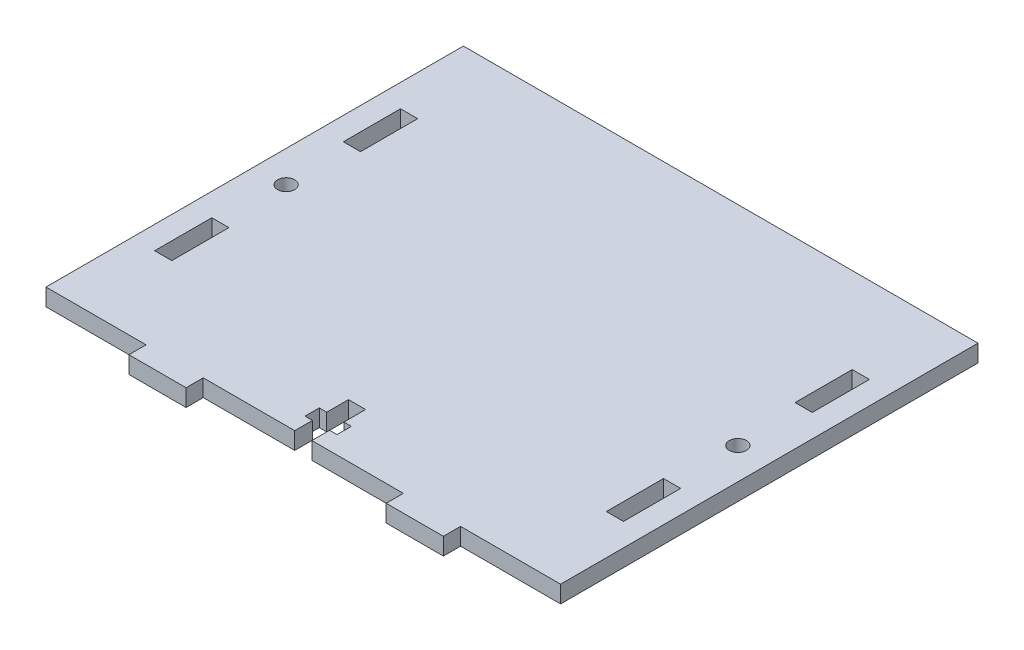
SolidWorks part; units mm, degrees
ref_plane "Front Plane" through (0, 0, 0) normal (0, 0, 1) x (1, 0, 0)
ref_plane "Top Plane" through (0, 0, 0) normal (0, 1, 0) x (1, 0, 0)
ref_plane "Right Plane" through (0, 0, 0) normal (1, 0, 0) x (0, 0, -1)
sketch "Sketch1" plane through (0, 0, 0) normal (0, 1, 0) x (1, 0, 0)
  line L0 (-72.5, 0) -> (-72.5, -3)
  line L1 (0, 0) -> (-17.5, 0)
  line L2 (0, 0) -> (0, 73)
  line L3 (0, 73) -> (-90, 73)
  line L4 (-90, 0) -> (-90, 73)
  line L5 (-72.5, -3) -> (-62.5, -3)
  line L6 (-62.5, -3) -> (-62.5, 0)
  line L7 (-72.5, 0) -> (-90, 0)
  line L8 (-45, 73) -> (-45, 9.4) construction
  line L9 (-17.5, 0) -> (-17.5, -3)
  line L10 (-17.5, -3) -> (-27.5, -3)
  line L11 (-27.5, -3) -> (-27.5, 0)
  line L12 (-27.5, 0) -> (-43.5, 0)
  line L13 (-46.5, 0) -> (-46.5, 3.1)
  line L14 (-46.5, 3.1) -> (-47.8, 3.1)
  line L15 (-47.8, 3.1) -> (-47.8, 5.6)
  line L16 (-47.8, 5.6) -> (-46.5, 5.6)
  line L17 (-46.5, -0.4668) -> (-46.5, 3.1)
  line L18 (-46.5, 5.6) -> (-46.5, 9.4)
  line L19 (-46.5, 9.4) -> (-43.5, 9.4)
  line L20 (-43.5, 9.4) -> (-43.5, 5.6)
  line L21 (-43.5, 5.6) -> (-42.2, 5.6)
  line L22 (-42.2, 5.6) -> (-42.2, 3.1)
  line L23 (-42.2, 3.1) -> (-43.5, 3.1)
  line L24 (-43.5, 3.1) -> (-43.5, 0)
  line L25 (-46.5, 0) -> (-62.5, 0)
  line L26 (-83, 15) -> (-86, 15)
  line L27 (-4, 15) -> (-4, 25)
  line L28 (-4, 25) -> (-7, 25)
  line L29 (-7, 25) -> (-7, 15)
  line L30 (-7, 15) -> (-4, 15)
  line L31 (-4, 48) -> (-7, 48)
  line L32 (-7, 48) -> (-7, 58)
  line L33 (-7, 58) -> (-4, 58)
  line L34 (-4, 58) -> (-4, 48)
  line L35 (-83, 25) -> (-83, 15)
  line L36 (-86, 15) -> (-86, 25)
  line L37 (-86, 25) -> (-83, 25)
  line L38 (-83, 48) -> (-83, 58)
  line L39 (-83, 58) -> (-86, 58)
  line L40 (-86, 58) -> (-86, 48)
  line L41 (-86, 48) -> (-83, 48)
  circle A0 centre (-5.5, 36.5) radius 1.5
  circle A1 centre (-84.5, 36.5) radius 1.5
  point P5 (-72.5, 0)
  point P11 (-5.5, 25)
  point P16 (-46.5, 0)
  point P31 (0, 15)
  dimension "D14" = 3
  dimension "D1" = 90
  dimension "D2" = 73
  dimension "D3" = 17.5
  dimension "D4" = 3
  dimension "D5" = 10
  dimension "D6" = 3.1
  dimension "D7" = 2.5
  dimension "D8" = 3.8
  dimension "D9" = 3
  dimension "D10" = 16
  dimension "D11" = 1.3
  dimension "D12" = 15
  dimension "D13" = 4
  dimension "D15" = 11.5
  dimension "D16" = 23
extrude "Boss-Extrude1" add sketch "Sketch1" along normal blind 3 contours L8 L3 L4 L7 L0 L5 L6 L25 L13 L14 L15 L16 L18 L19 L36 L37 L35 L26 L41 L40 L39 L38 A1 | L3 L8 L19 L20 L21 L22 L23 L24 L12 L11 L10 L9 L1 L2 A0 L30 L29 L28 L27 L33 L34 L31 L32
